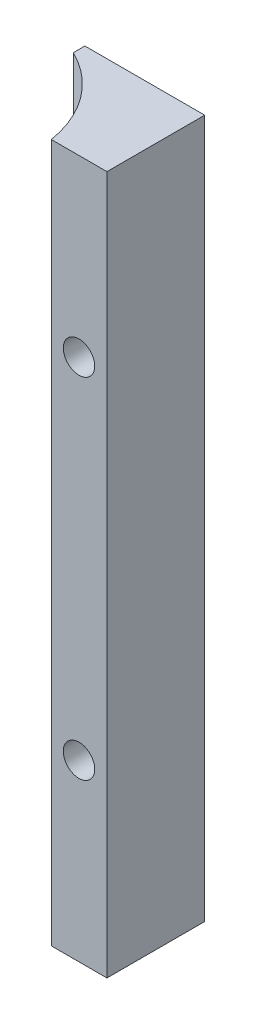
SolidWorks part; units mm, degrees
ref_plane "Front" through (0, 0, 0) normal (0, 0, 1) x (1, 0, 0)
ref_plane "Top" through (0, 0, 0) normal (0, 1, 0) x (1, 0, 0)
ref_plane "Right" through (0, 0, 0) normal (1, 0, 0) x (0, 0, -1)
sketch "Sketch1" plane through (0, 0, 0) normal (0, 1, 0) x (1, 0, 0)
  line L0 (0, 0) -> (0, 8.4)
  line L1 (0, 8.4) -> (-10.2923, 8.4)
  line L2 (-10.2923, 8.4) -> (-10.2923, 7.4)
  line L3 (-4.78, 0) -> (0, 0)
  arc A0 (-10.2923, 7.4) -> (-4.78, 0) centre (-14.6512, -1.6) cw
  dimension "D3" = 10
  dimension "D1" = 4.78
  dimension "D2" = 8.4
  dimension "D4" = 1.6
  dimension "D5" = 1
extrude "Boss-Extrude1" add sketch "Sketch1" along normal blind 60
sketch "Sketch2" plane through (0, 0, 0) normal (0, 0, 1) x (1, 0, 0)
  line L0 (-2.4, 60) -> (-2.4, 0) construction
  line L1 (-4.78, 60) -> (0, 60) construction
  line L2 (-4.78, 0) -> (0, 0) construction
  line L4 (-4.78, 60) -> (-4.78, 0) construction
  point P6 (-2.4, 45)
  point P7 (-2.4, 15)
  dimension "D1" = 15
  dimension "D2" = 15
  dimension "D3" = 2.38
hole_wizard "Ø2.7 (2.7) Diameter Hole1" positions "3DSketch1" profile "Sketch3" hole size "Ø2.7" standard "ANSI Metric" end condition up to next
sketch3d "3DSketch1"
  point P0 (-2.4, 45, 0)
  point P3 (-2.4, 15, 0)
sketch "Sketch3" plane through (-2.4, 45, 0) normal (1, 0, 0) x (0, -1, 0)
  line L0 (0, 0) -> (0, 8.4)
  line L1 (0, 8.4) -> (1.35, 8.4)
  line L2 (1.35, 8.4) -> (1.35, 0)
  line L5 (1.35, 0) -> (0, 0)
  line L11 (0, -6.35) -> (0, 107.95) construction
  dimension "Thru Hole Dia." = 2.7
  dimension "Thru Hole Depth" = 8.4
